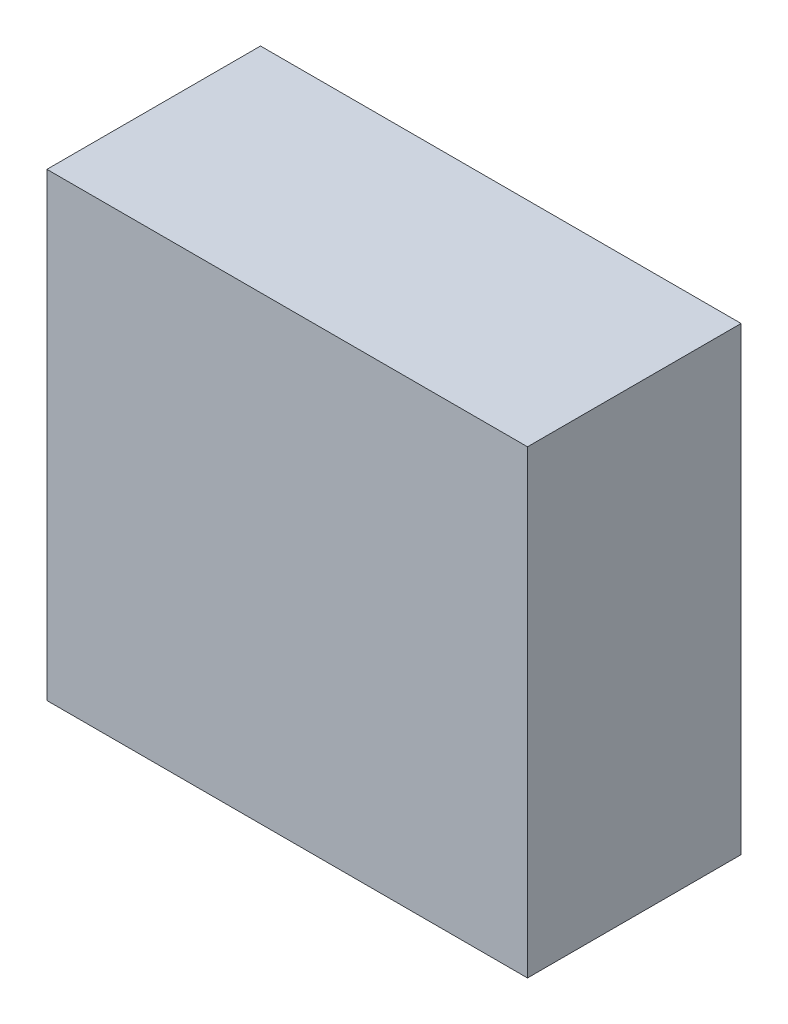
SolidWorks part; units mm, degrees
ref_plane "前视基准面" through (0, 0, 0) normal (0, 0, 1) x (1, 0, 0)
ref_plane "上视基准面" through (0, 0, 0) normal (0, 1, 0) x (1, 0, 0)
ref_plane "右视基准面" through (0, 0, 0) normal (1, 0, 0) x (0, 0, -1)
sketch "草图1" plane through (0, 0, 0) normal (0, 0, 1) x (1, 0, 0)
  line L1 (-58.5, -56) -> (58.5, -56)
  line L2 (-58.5, -56) -> (-58.5, 56)
  line L3 (-58.5, 56) -> (58.5, 56)
  line L4 (58.5, -56) -> (58.5, 56)
  line L5 (-58.5, -56) -> (58.5, 56) construction
  line L6 (-58.5, 56) -> (58.5, -56) construction
  point P0 (0, 0)
  dimension "D1" = 117
  dimension "D2" = 112
extrude "凸台-拉伸1" add sketch "草图1" along normal blind 52 contours L3 L4 L1 L2
